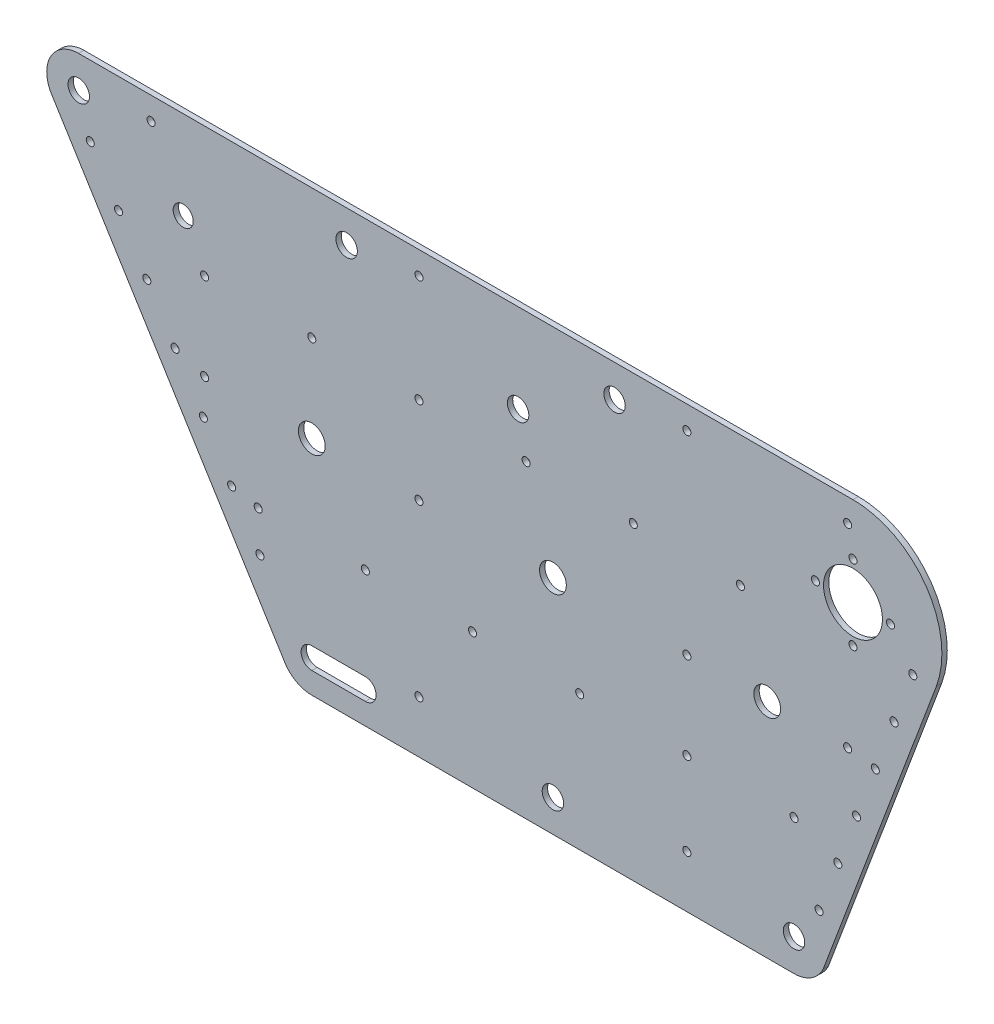
SolidWorks part; units mm, degrees
ref_plane "Front Plane" through (0, 0, 0) normal (0, 0, 1) x (1, 0, 0)
ref_plane "Top Plane" through (0, 0, 0) normal (0, 1, 0) x (1, 0, 0)
ref_plane "Right Plane" through (0, 0, 0) normal (1, 0, 0) x (0, 0, -1)
sketch "Sketch6" plane through (0, 0, 0) normal (0, 0, 1) x (1, 0, 0)
  line L0 (-106.0052, 144.9436) -> (182.9631, 145.1977)
  line L1 (160.992, -19) -> (-18.999, -19)
  line L2 (171.9001, -12) -> (214.069, 100.3323)
  line L3 (-18.999, -3) -> (1, -3)
  line L4 (0.9999, -11) -> (-18.9991, -11)
  line L5 (-29.7001, -12.4286) -> (-116.0855, 126.6112)
  line L6 (-18.9991, -18) -> (-18.8768, -17.9993)
  ellipse E0 centre (-105.9947, 133) end of major axis (-105.9947, 137) minor radius 3.9998
  ellipse E1 centre (160.992, -7) end of major axis (160.992, -3) minor radius 3.9998
  ellipse E2 centre (-18.9991, -7) end of major axis (-18.9991, -11) minor radius 3.9998 (-18.999, -3) -> (-18.9991, -11) ccw
  ellipse E3 centre (182.9908, 112) end of major axis (182.9908, 123) minor radius 10.9995
  ellipse E4 centre (-105.9947, 133) end of major axis (-105.9947, 144.9436) minor radius 11.943 (-106.0052, 144.9436) -> (-116.0855, 126.6112) ccw
  ellipse E5 centre (182.9908, 112) end of major axis (182.9909, 145.1977) minor radius 33.196 (214.069, 100.3323) -> (182.9617, 145.1977) ccw
  ellipse E6 centre (1, -7) end of major axis (1, -3) minor radius 3.9998 (0.9999, -11) -> (1, -3) ccw
  ellipse E7 centre (182.9908, 126) end of major axis (182.9908, 127.5) minor radius 1.4999
  ellipse E8 centre (196.9901, 112) end of major axis (196.9901, 113.5) minor radius 1.4999
  ellipse E9 centre (168.9915, 112) end of major axis (168.9915, 113.5) minor radius 1.4999
  ellipse E10 centre (182.9908, 98) end of major axis (182.9908, 99.5) minor radius 1.4999
  ellipse E11 centre (-18.9991, -7) end of major axis (-18.999, 5) minor radius 11.9994 (-29.7019, -12.4256) -> (-18.999, -19) ccw
  ellipse E12 centre (160.992, -7) end of major axis (160.992, 5) minor radius 11.9994 (160.992, -19) -> (171.9001, -12) ccw
  ellipse E13 centre (120.9939, 0.5) end of major axis (120.994, 2) minor radius 1.4999
  ellipse E14 centre (20.9989, 0.5) end of major axis (20.9989, 2) minor radius 1.4999
  ellipse E15 centre (120.9939, 64) end of major axis (120.994, 65.5) minor radius 1.4999
  ellipse E16 centre (20.9989, 64) end of major axis (20.9989, 65.5) minor radius 1.4999
  ellipse E17 centre (-58.997, 64) end of major axis (-58.997, 65.5) minor radius 1.4999
  ellipse E18 centre (180.9909, 64) end of major axis (180.9909, 65.5) minor radius 1.4999
  ellipse E19 centre (-78.996, 136.5) end of major axis (-78.996, 138) minor radius 1.4999
  ellipse E20 centre (20.9989, 136.5) end of major axis (20.9989, 138) minor radius 1.4999
  ellipse E21 centre (120.9939, 136.5) end of major axis (120.994, 138) minor radius 1.4999
  ellipse E22 centre (60.9969, 96.5) end of major axis (60.9969, 98) minor radius 1.4999
  ellipse E23 centre (140.9929, 96.5) end of major axis (140.9929, 98) minor radius 1.4999
  ellipse E24 centre (160.992, 31.5) end of major axis (160.992, 33) minor radius 1.4999
  ellipse E25 centre (80.996, 31.5) end of major axis (80.996, 33) minor radius 1.4999
  ellipse E26 centre (-18.9991, 96.5) end of major axis (-18.9991, 98) minor radius 1.4999
  ellipse E27 centre (-38.998, 31.5) end of major axis (-38.998, 33) minor radius 1.4999
  ellipse E28 centre (-18.9991, 64) end of major axis (-18.999, 69) minor radius 4.9997
  ellipse E29 centre (70.9964, 64) end of major axis (70.9965, 69) minor radius 4.9997
  ellipse E30 centre (150.9924, 64) end of major axis (150.9924, 69) minor radius 4.9997
  ellipse E31 centre (-101.6892, 118.5984) end of major axis (-101.6892, 120.0984) minor radius 1.4999
  ellipse E32 centre (-91.1347, 101.6106) end of major axis (-91.1347, 103.1106) minor radius 1.4999
  ellipse E33 centre (-80.5803, 84.623) end of major axis (-80.5803, 86.123) minor radius 1.4999
  ellipse E34 centre (-70.0255, 67.6347) end of major axis (-70.0255, 69.1347) minor radius 1.4999
  ellipse E35 centre (-59.4708, 50.6466) end of major axis (-59.4708, 52.1466) minor radius 1.4999
  ellipse E36 centre (-48.9163, 33.6588) end of major axis (-48.9163, 35.1588) minor radius 1.4999
  ellipse E37 centre (-38.3619, 16.6713) end of major axis (-38.3619, 18.1713) minor radius 1.4999
  ellipse E38 centre (205.3225, 99.7958) end of major axis (205.3225, 101.2958) minor radius 1.4999
  ellipse E39 centre (198.3244, 81.0602) end of major axis (198.3244, 82.5602) minor radius 1.4999
  ellipse E40 centre (191.3265, 62.3248) end of major axis (191.3265, 63.8248) minor radius 1.4999
  ellipse E41 centre (184.3286, 43.5896) end of major axis (184.3286, 45.0896) minor radius 1.4999
  ellipse E42 centre (177.3307, 24.8545) end of major axis (177.3307, 26.3545) minor radius 1.4999
  ellipse E43 centre (170.3325, 6.1186) end of major axis (170.3325, 7.6186) minor radius 1.4999
  ellipse E44 centre (180.9909, 136.5) end of major axis (180.9909, 138) minor radius 1.4999
  ellipse E45 centre (20.9989, 96.5) end of major axis (20.9989, 98) minor radius 1.4999
  ellipse E46 centre (100.995, 96.5) end of major axis (100.995, 98) minor radius 1.4999
  ellipse E47 centre (-58.9971, 96.5) end of major axis (-58.997, 98) minor radius 1.4999
  ellipse E48 centre (0.9999, 31.5) end of major axis (1, 33) minor radius 1.4999
  ellipse E49 centre (40.9979, 31.5) end of major axis (40.9979, 33) minor radius 1.4999
  ellipse E50 centre (120.9939, 31.5) end of major axis (120.994, 33) minor radius 1.4999
  ellipse E51 centre (-66.9967, 112) end of major axis (-66.9966, 115.75) minor radius 3.7498
  ellipse E52 centre (57.9971, 112) end of major axis (57.9971, 116) minor radius 3.9998
  ellipse E53 centre (-5.9997, 133) end of major axis (-5.9997, 137) minor radius 3.9998
  ellipse E54 centre (93.9952, 133) end of major axis (93.9952, 137) minor radius 3.9998
  ellipse E55 centre (70.9964, -7) end of major axis (70.9965, -3) minor radius 3.9998
  point P0 (0, 0.001)
  point P1 (0.001, 0.001)
  point P2 (0.001, 0)
ref_plane "Plane1" through (0, 0, 0) normal (0, 0, -1) x (-1, 0, 0)
extrude "Boss-Extrude4" add sketch "Sketch6" along normal mid plane 2
